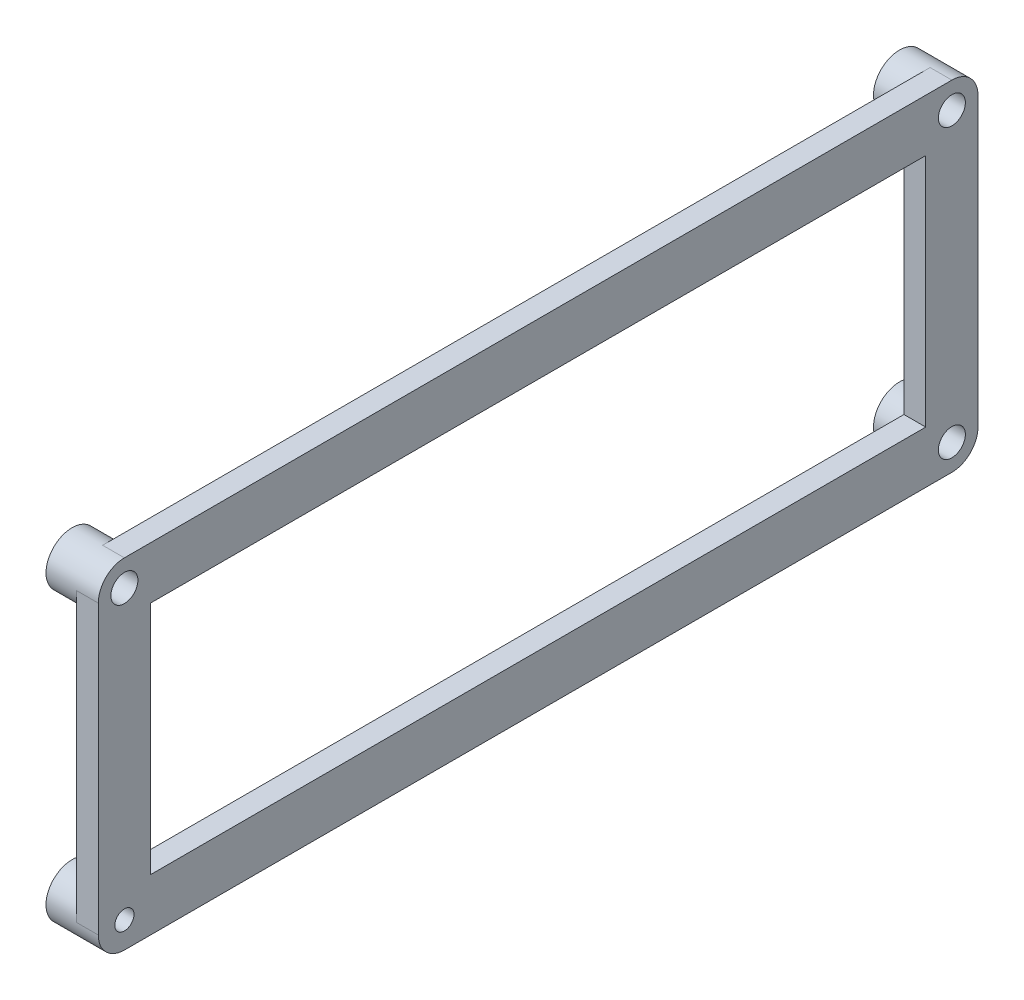
SolidWorks part; units mm, degrees
ref_plane "Front Plane" through (0, 0, 0) normal (0, 0, 1) x (1, 0, 0)
ref_plane "Top Plane" through (0, 0, 0) normal (0, 1, 0) x (1, 0, 0)
ref_plane "Right Plane" through (0, 0, 0) normal (1, 0, 0) x (0, 0, -1)
sketch "Sketch1" plane through (0, 0, 0) normal (1, 0, 0) x (0, 0, -1)
  line L1 (-47.5, -16.5) -> (47.5, -16.5) construction
  line L2 (-47.5, -16.5) -> (-47.5, 16.5) construction
  line L3 (-47.5, 16.5) -> (47.5, 16.5) construction
  line L4 (47.5, -16.5) -> (47.5, 16.5) construction
  line L5 (-47.5, -16.5) -> (47.5, 16.5) construction
  line L6 (-47.5, 16.5) -> (47.5, -16.5) construction
  circle A0 centre (-47.5, 16.5) radius 1.55
  circle A1 centre (-47.5, -16.5) radius 1.55
  circle A2 centre (47.5, -16.5) radius 1.55
  circle A3 centre (47.5, 16.5) radius 1.55
  circle A4 centre (-47.5, 16.5) radius 3
  circle A5 centre (-47.5, -16.5) radius 3
  circle A6 centre (47.5, -16.5) radius 3
  circle A7 centre (47.5, 16.5) radius 3
  point P0 (0, 0)
  dimension "D3" = 3.1
  dimension "D4" = 6
  dimension "D1" = 95
  dimension "D2" = 33
extrude "Boss-Extrude1" add sketch "Sketch1" along normal blind 3.5
sketch "Sketch2" plane through (3.5, 0, 0) normal (1, 0, 0) x (0, 0, -1)
  line L0 (-47.5, 19.5) -> (47.5, 19.5)
  line L1 (50.5, 16.5) -> (50.5, -16.5)
  line L2 (-47.5, 13.5) -> (47.5, 13.5)
  line L3 (44.5, 16.5) -> (44.5, -16.5)
  line L4 (-47.5, -13.5) -> (47.5, -13.5)
  line L5 (-47.5, -19.5) -> (47.5, -19.5)
  line L6 (-50.5, 16.5) -> (-50.5, -16.5)
  line L7 (-44.5, 16.5) -> (-44.5, -16.5)
  circle A1 centre (47.5, 16.5) radius 3
  circle A2 centre (47.5, 16.5) radius 3
  circle A3 centre (47.5, -16.5) radius 3
  circle A4 centre (47.5, -16.5) radius 3
  circle A5 centre (-47.5, -16.5) radius 3
  circle A6 centre (-47.5, -16.5) radius 3
  circle A7 centre (-47.5, 16.5) radius 3
  circle A8 centre (-47.5, 16.5) radius 3
  circle A9 centre (47.5, 16.5) radius 1.55
  circle A10 centre (47.5, 16.5) radius 1.55
  circle A11 centre (47.5, -16.5) radius 1.55
  circle A12 centre (47.5, -16.5) radius 1.55
  circle A13 centre (-47.5, -16.5) radius 1.55
  circle A14 centre (-47.5, -16.5) radius 1.55
  circle A15 centre (-47.5, 16.5) radius 1.55
  circle A16 centre (-47.5, 16.5) radius 1.55
  circle M9 centre (-47.5, 16.5) radius 3
  circle M10 centre (-47.5, 16.5) radius 1.55
  dimension "D1" = 0
  dimension "D2" = 0
  dimension "D3" = 0
  dimension "D4" = 0
  dimension "D5" = 0
  dimension "D6" = 0
  dimension "D7" = 0
  dimension "D8" = 0
extrude "Boss-Extrude2" add sketch "Sketch2" along normal blind 2.5 contours A2 L0 L7 L2 L3 M9 | M9 M10 | L7 L2 M9 | A6 L4 L7 L2 L6 M9 | A6 L7 L4 | A6 L5 A4 L3 L4 L7 | A6 A14 | A4 L1 A2 L2 L3 L4 | A4 L4 L3 | A4 A12 | A2 L3 L2 | A2 A10
sketch "Sketch3" plane through (6, 0, 0) normal (1, 0, 0) x (0, 0, -1)
  line L0 (50.5, 16.5) -> (50.5, -16.5) construction
  line L1 (44.5, -13.5) -> (50.5, -13.5)
  line L2 (44.5, -13.5) -> (44.5, -7.5)
  line L3 (44.5, -7.5) -> (50.5, -7.5)
  line L4 (50.5, -13.5) -> (50.5, -7.5)
  line L5 (-50.5, 16.5) -> (-50.5, -16.5) construction
  line L6 (-44.5, -13.5) -> (-50.5, -13.5)
  line L7 (-44.5, -13.5) -> (-44.5, -7.5)
  line L8 (-44.5, -7.5) -> (-50.5, -7.5)
  line L9 (-50.5, -13.5) -> (-50.5, -7.5)
  dimension "D1" = 6
extrude "Boss-Extrude3" add sketch "Sketch3" along normal blind 5
sketch "Sketch4" plane through (11, 0, 0) normal (1, 0, 0) x (0, 0, -1)
  line L1 (44.5, -7.5) -> (50.5, -7.5)
  line L2 (44.5, -7.5) -> (44.5, -22.5)
  line L3 (44.5, -22.5) -> (50.5, -22.5)
  line L4 (50.5, -7.5) -> (50.5, -22.5)
  dimension "D1" = 15
extrude "Boss-Extrude4" add sketch "Sketch4" along normal blind 2.5
sketch "Sketch5" plane through (0, 0, 50.5) normal (0, 0, 1) x (1, 0, 0)
  line L0 (11, -13.5) -> (6, -13.5) construction
  line L1 (11, -7.5) -> (7, -7.5)
  line L2 (11, -7.5) -> (11, -13.5)
  line L3 (11, -13.5) -> (7, -13.5)
  line L4 (7, -7.5) -> (7, -13.5)
  dimension "D1" = 4
extrude "Boss-Extrude5" add sketch "Sketch5" along normal up to surface (21.9 mm away)
sketch "Sketch6" plane through (11, 0, 0) normal (1, 0, 0) x (0, 0, -1)
  line L0 (-65.7, -7.5) -> (-65.7, -40.3) construction
  line L1 (-72.4, -7.5) -> (-65.7, -7.5)
  line L2 (-72.4, -7.5) -> (-72.4, -22.5)
  line L3 (-72.4, -22.5) -> (-65.7, -22.5)
  line L4 (-65.7, -7.5) -> (-65.7, -22.5)
  line L5 (44.5, -22.5) -> (50.5, -22.5) construction
extrude "Boss-Extrude6" add sketch "Sketch6" along normal blind 2.5
ref_plane "Plane1" through (6, 0, 0) normal (1, 0, 0) x (0, 0, -1)
split "Split1" trim tools "Plane1" bodies to split 109 resulting bodies 110 111 112
delete or keep bodies "Body-Delete/Keep 1" [suppressed] type delete bodies bodies 110 111
delete or keep bodies "Body-Delete/Keep 2" type delete bodies bodies 110 111
sketch "Sketch7" plane through (0, 0, 0) normal (-1, 0, 0) x (0, 0, 1)
  circle A0 centre (47.5, -16.5) radius 1.1
  circle A1 centre (47.5, -16.5) radius 1.55 construction
  circle A2 centre (47.5, -16.5) radius 1.55
  dimension "D1" = 2.2
extrude "Boss-Extrude7" add sketch "Sketch7" against normal up to surface (6 mm away) up to face at (6, 0, 0)
